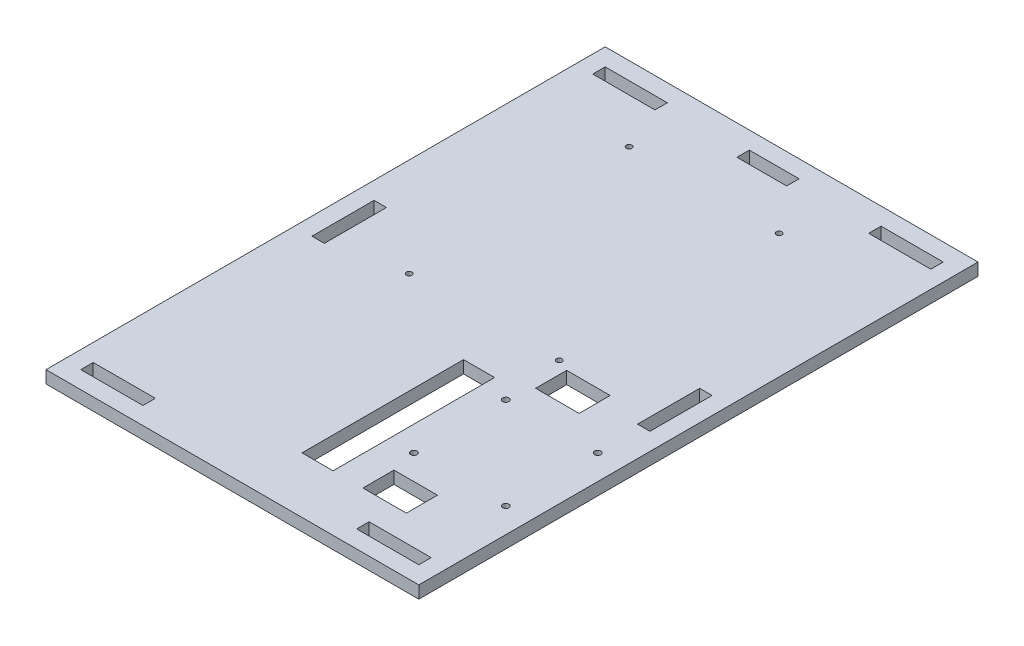
SolidWorks part; units mm, degrees
ref_plane "Front Plane" through (0, 0, 0) normal (0, 0, 1) x (1, 0, 0)
ref_plane "Top Plane" through (0, 0, 0) normal (0, 1, 0) x (1, 0, 0)
ref_plane "Right Plane" through (0, 0, 0) normal (1, 0, 0) x (0, 0, -1)
sketch "Sketch1" plane through (0, 0, 0) normal (0, 1, 0) x (1, 0, 0)
  line L1 (-75, 112.5) -> (75, 112.5)
  line L2 (-75, 112.5) -> (-75, -112.5)
  line L3 (-75, -112.5) -> (75, -112.5)
  line L4 (75, 112.5) -> (75, -112.5)
  point P4 (0, 112.5)
  point P6 (-75, 0)
  dimension "D1" = 150
  dimension "D2" = 225
extrude "Boss-Extrude1" add sketch "Sketch1" along normal blind 5
sketch "Sketch2" plane through (0, 5, 0) normal (0, 1, 0) x (1, 0, 0)
  line L0 (-35.35, 82.5) -> (25, 82.5) construction
  line L1 (-35.35, 82.5) -> (-35.35, -6) construction
  circle A0 centre (-35.35, 82.5) radius 1.125
  circle A1 centre (25, 82.5) radius 1.125
  circle A2 centre (25, -6) radius 1.125
  circle A3 centre (-35.35, -6) radius 1.125
  point P8 (-66.2804, -34.6141)
  point P15 (-66.3443, -35.1492)
  point P16 (-67.1717, -39.584)
  dimension "D3" = 2.25
  dimension "D1" = 60.35
  dimension "D2" = 88.5
  dimension "D4" = 30
  dimension "D5" = 50
sketch "Sketch3" plane through (0, 5, 0) normal (0, 1, 0) x (1, 0, 0)
  line L0 (28, -30.5) -> (28, -67.5) construction
  line L1 (28, -30.5) -> (65, -30.5) construction
  circle A0 centre (28, -30.5) radius 1.275
  circle A1 centre (65, -30.5) radius 1.275
  circle A2 centre (65, -67.5) radius 1.275
  circle A3 centre (28, -67.5) radius 1.275
  point P11 (71.7548, -73.6513)
  dimension "D1" = 2.55
  dimension "D2" = 37
  dimension "D3" = 45
  dimension "D4" = 10
sketch "Sketch6" plane through (0, 5, 0) normal (0, 1, 0) x (1, 0, 0)
  line L10 (-10, 105.5) -> (10, 105.5)
  line L11 (-10, 105.5) -> (-10, 100.5)
  line L12 (-10, 100.5) -> (10, 100.5)
  line L13 (10, 105.5) -> (10, 100.5)
  point P4 (0, 105.5)
  dimension "D1" = 20
  dimension "D2" = 7
  dimension "D3" = 5
extrude "Cut-Extrude1" cut sketch "Sketch2" against normal through all
extrude "Cut-Extrude2" cut sketch "Sketch3" against normal through all
extrude "Cut-Extrude3" cut sketch "Sketch6" against normal through all
sketch "Sketch9" plane through (0, 5, 0) normal (0, 1, 0) x (1, 0, 0)
  line L1 (5.5, -90) -> (18, -90)
  line L2 (5.5, -90) -> (5.5, -25)
  line L3 (5.5, -25) -> (18, -25)
  line L4 (18, -90) -> (18, -25)
  line L5 (30, -8) -> (47.5, -8)
  line L6 (30, -8) -> (30, -20.5)
  line L7 (30, -20.5) -> (47.5, -20.5)
  line L8 (47.5, -8) -> (47.5, -20.5)
  line L9 (30, -77.5) -> (47.5, -77.5)
  line L10 (30, -77.5) -> (30, -90)
  line L11 (30, -90) -> (47.5, -90)
  line L12 (47.5, -77.5) -> (47.5, -90)
  circle A0 centre (28, -30.5) radius 1.275 construction
  circle A1 centre (28, -67.5) radius 1.275 construction
  dimension "D1" = 2
  dimension "D5" = 10
  dimension "D2" = 12.5
  dimension "D3" = 17.5
  dimension "D4" = 10
  dimension "D6" = 10
  dimension "D7" = 12.5
  dimension "D8" = 65
extrude "Cut-Extrude4" cut sketch "Sketch9" against normal up to surface (5 mm away) up to face at (0, 0, -103)
sketch "Sketch10" plane through (0, 5, 0) normal (0, 1, 0) x (1, 0, 0)
  line L0 (0, 0) -> (-75, 0) construction
  line L1 (-68, -105.5) -> (-43, -105.5)
  line L2 (-68, -105.5) -> (-68, -100.5)
  line L3 (-68, -100.5) -> (-43, -100.5)
  line L4 (-43, -105.5) -> (-43, -100.5)
  line L9 (-75, 112.5) -> (-75, -112.5) construction
  line L10 (0, 0) -> (0, -112.5) construction
  line L11 (-75, -112.5) -> (75, -112.5) construction
  line L12 (-68, 100.5) -> (-43, 100.5)
  line L13 (-43, 105.5) -> (-43, 100.5)
  line L14 (-68, 105.5) -> (-43, 105.5)
  line L15 (-68, 105.5) -> (-68, 100.5)
  line L16 (68, -100.5) -> (43, -100.5)
  line L17 (43, -105.5) -> (43, -100.5)
  line L18 (68, -105.5) -> (43, -105.5)
  line L19 (68, -105.5) -> (68, -100.5)
  line L20 (68, 105.5) -> (68, 100.5)
  line L21 (68, 105.5) -> (43, 105.5)
  line L22 (43, 105.5) -> (43, 100.5)
  line L23 (68, 100.5) -> (43, 100.5)
  line L24 (68, -12.5) -> (63, -12.5)
  line L25 (-68, 12.5) -> (-63, 12.5)
  line L26 (-68, 12.5) -> (-68, -12.5)
  line L27 (-68, -12.5) -> (-63, -12.5)
  line L28 (-63, 12.5) -> (-63, -12.5)
  line L29 (63, 12.5) -> (63, -12.5)
  line L30 (68, 12.5) -> (63, 12.5)
  line L31 (68, 12.5) -> (68, -12.5)
  point P29 (-68, 0)
  dimension "D1" = 7
  dimension "D2" = 7
  dimension "D3" = 5
  dimension "D4" = 25
extrude "Cut-Extrude5" cut sketch "Sketch10" against normal up to surface (5 mm away) up to face at (11.75, 0, 57.5)
